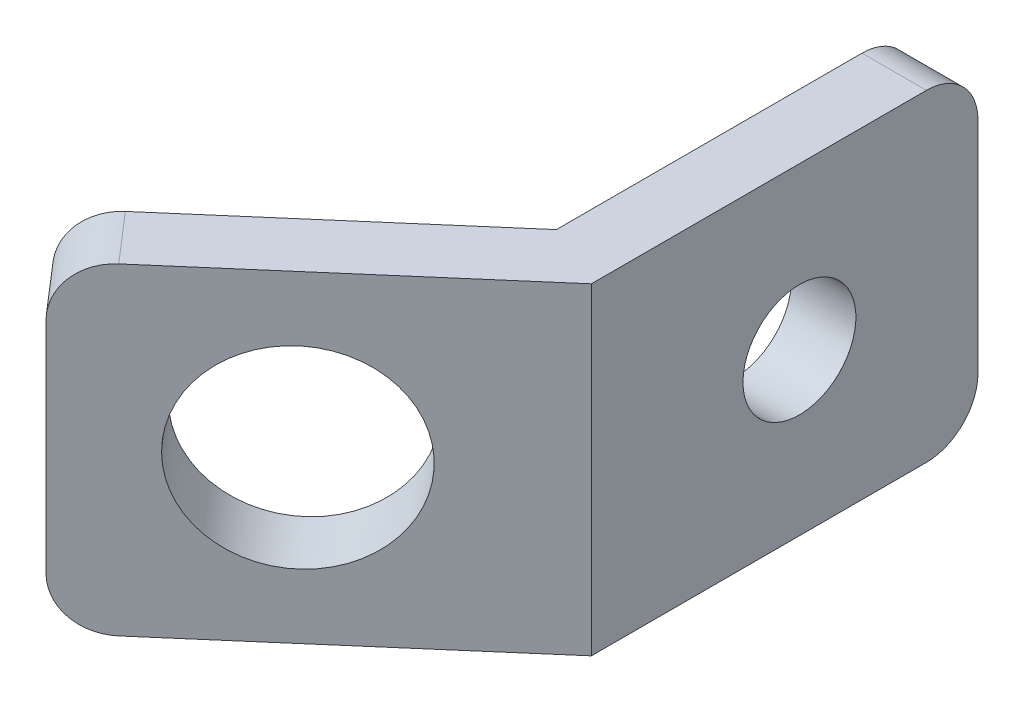
SolidWorks part; units mm, degrees
ref_plane "Front Plane" through (0, 0, 0) normal (0, 0, 1) x (1, 0, 0)
ref_plane "Top Plane" through (0, 0, 0) normal (0, 1, 0) x (1, 0, 0)
ref_plane "Right Plane" through (0, 0, 0) normal (1, 0, 0) x (0, 0, -1)
sketch "Sketch1" plane through (0, 0, 0) normal (0, 1, 0) x (1, 0, 0)
  line L0 (0, 0) -> (0, 19.05)
  line L1 (0, 19.05) -> (-3.175, 19.05)
  line L2 (-3.175, 19.05) -> (-3.175, 1.4528)
  line L3 (-3.175, 1.4528) -> (-16.491, -10.0514)
  line L4 (-16.491, -10.0514) -> (-14.4153, -12.4539)
  line L5 (-14.4153, -12.4539) -> (0, 0)
  dimension "D1" = 3.175
  dimension "D2" = 3.175
  dimension "D3" = 19.05
  dimension "D4" = 19.05
extrude "Boss-Extrude1" add sketch "Sketch1" along normal blind 15.875
sketch "Sketch3" plane through (-3.175, 0, 0) normal (-1, 0, 0) x (0, 0, 1)
  line L0 (-10.2514, 15.875) -> (-10.2514, 0) construction
  line L1 (-19.05, 15.875) -> (-1.4528, 15.875) construction
  line L2 (-19.05, 0) -> (-1.4528, 0) construction
  circle A0 centre (-10.2514, 7.9375) radius 2.7813
  dimension "D1" = 5.5626
extrude "Cut-Extrude1" cut sketch "Sketch3" against normal through all
sketch "Sketch4" plane through (-2.0757, 0, -2.4026) normal (-0.6537, 0, -0.7567) x (-0.7567, 0, 0.6537)
  line L0 (10.2514, 0) -> (10.2514, 15.875) construction
  line L1 (1.4528, 0) -> (19.05, 0) construction
  line L2 (1.4528, 15.875) -> (19.05, 15.875) construction
  circle A0 centre (10.2514, 7.9375) radius 4.7625
  dimension "D1" = 9.525
extrude "Cut-Extrude2" cut sketch "Sketch4" against normal through all
fillet "Fillet1" radius 2.54 4 edges at (-1.5875, 15.875, -19.05) (-1.5875, 0, -19.05) (-15.4532, 0, 11.2527) (-15.4532, 15.875, 11.2527)
